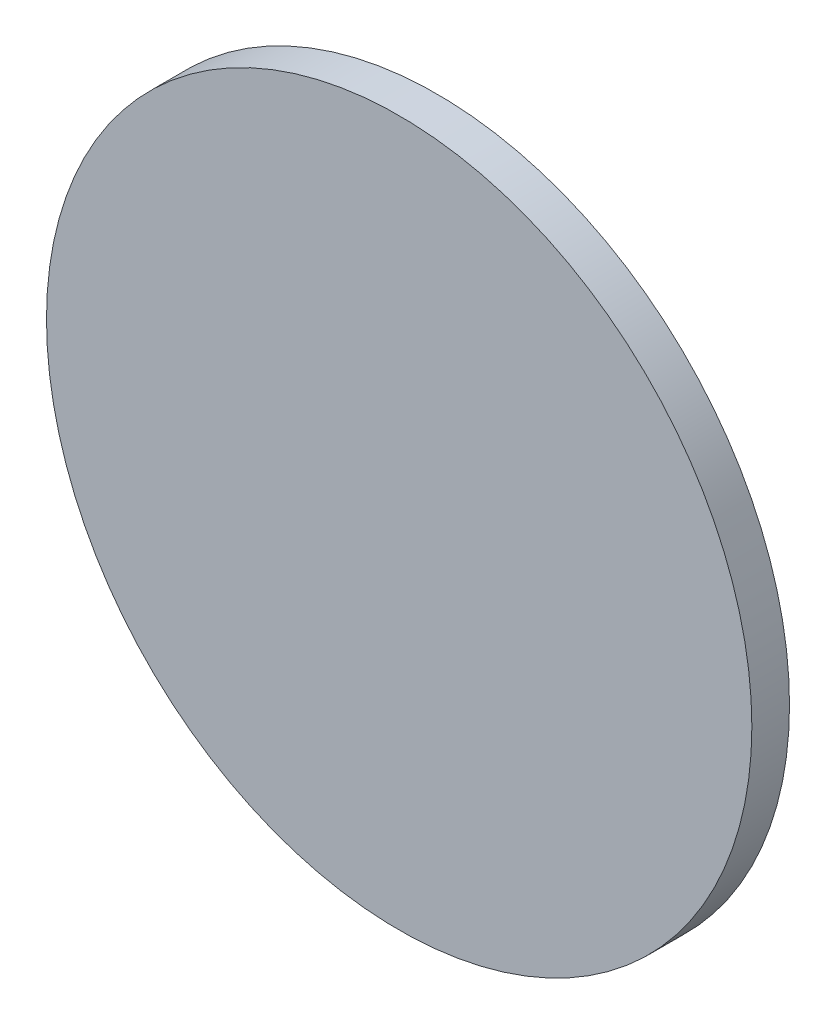
SolidWorks part; units mm, degrees
ref_plane "Front Plane" through (0, 0, 0) normal (0, 0, 1) x (1, 0, 0)
ref_plane "Top Plane" through (0, 0, 0) normal (0, 1, 0) x (1, 0, 0)
ref_plane "Right Plane" through (0, 0, 0) normal (1, 0, 0) x (0, 0, -1)
sketch "Sketch1" plane through (0, 0, 0) normal (0, 0, 1) x (1, 0, 0)
  circle A0 centre (0, 0) radius 14.8
  dimension "D1" = 29.6
extrude "Boss-Extrude1" add sketch "Sketch1" along normal blind 1.58
sketch "Sketch2" plane through (0, 0, 0) normal (0, 0, -1) x (-1, 0, 0)
  circle A0 centre (0, 0) radius 10.95
  dimension "D1" = 21.9
